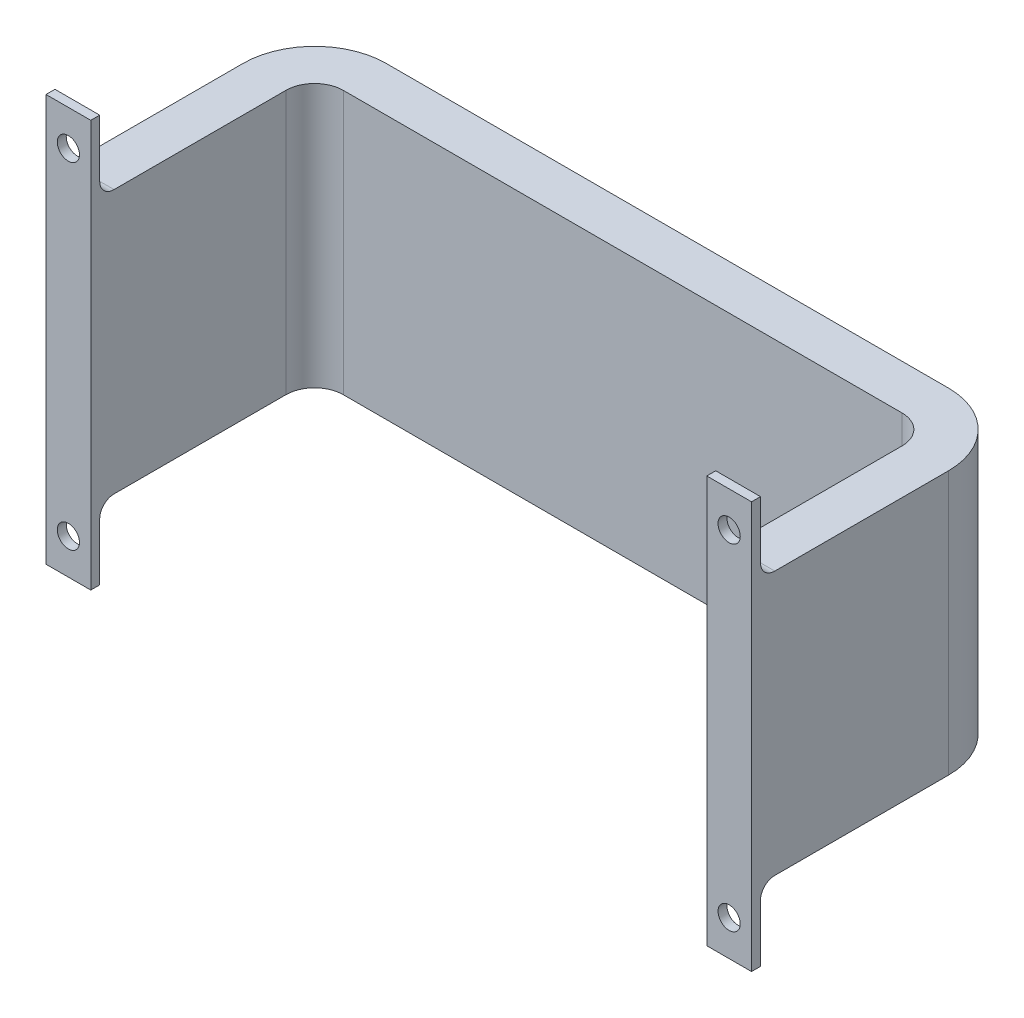
SolidWorks part; units mm, degrees
material "1060 Alloy"
ref_plane "Front Plane" through (0, 0, 0) normal (0, 0, 1) x (1, 0, 0)
ref_plane "Top Plane" through (0, 0, 0) normal (0, 1, 0) x (1, 0, 0)
ref_plane "Right Plane" through (0, 0, 0) normal (1, 0, 0) x (0, 0, -1)
sketch "Sketch1" plane through (0, 0, 0) normal (0, 0, 1) x (1, 0, 0)
  line L1 (125.095, -46.736) -> (-125.095, -46.736)
  line L2 (125.095, -46.736) -> (125.095, 46.736)
  line L3 (125.095, 46.736) -> (-125.095, 46.736)
  line L4 (-125.095, -46.736) -> (-125.095, 46.736)
  line L5 (125.095, -46.736) -> (-125.095, 46.736) construction
  line L6 (125.095, 46.736) -> (-125.095, -46.736) construction
  point P0 (0, 0)
  dimension "D1" = 93.472
  dimension "D2" = 250.19
extrude "Boss-Extrude1" add sketch "Sketch1" along normal blind 95.25
sketch "Sketch5" plane through (0, 0, 95.25) normal (0, 0, 1) x (1, 0, 0)
  line L1 (109.22, -46.736) -> (-109.22, -46.736)
  line L2 (109.22, -46.736) -> (109.22, 46.736)
  line L3 (109.22, 46.736) -> (-109.22, 46.736)
  line L4 (-109.22, -46.736) -> (-109.22, 46.736)
  line L5 (109.22, -46.736) -> (-109.22, 46.736) construction
  line L6 (109.22, 46.736) -> (-109.22, -46.736) construction
  point P0 (0, 0)
  dimension "D1" = 93.472
  dimension "D2" = 218.44
extrude "Cut-Extrude1" cut sketch "Sketch5" against normal blind 79.375
sketch "Sketch6" plane through (0, 0, 95.25) normal (0, 0, 1) x (1, 0, 0)
  line L1 (109.22, 72.136) -> (125.095, 72.136)
  line L2 (109.22, 72.136) -> (109.22, 46.736)
  line L3 (109.22, 46.736) -> (125.095, 46.736)
  line L4 (125.095, 72.136) -> (125.095, 46.736)
  line L5 (109.22, 72.136) -> (125.095, 46.736) construction
  line L6 (109.22, 46.736) -> (125.095, 72.136) construction
  line L8 (125.095, 46.736) -> (109.22, 46.736) construction
  line L9 (125.095, -46.736) -> (125.095, 46.736) construction
  line L11 (0, -51.4096) -> (0, 51.4096) construction
  line L12 (-109.22, 46.736) -> (-125.095, 46.736)
  line L13 (-125.095, 72.136) -> (-125.095, 46.736)
  line L14 (-109.22, 72.136) -> (-125.095, 72.136)
  line L15 (-109.22, 72.136) -> (-109.22, 46.736)
  line L16 (52.3875, 0) -> (-52.3875, 0) construction
  line L17 (109.22, -46.736) -> (125.095, -46.736)
  line L18 (125.095, -72.136) -> (125.095, -46.736)
  line L19 (109.22, -72.136) -> (125.095, -72.136)
  line L20 (109.22, -72.136) -> (109.22, -46.736)
  line L21 (-109.22, -72.136) -> (-109.22, -46.736)
  line L22 (-109.22, -72.136) -> (-125.095, -72.136)
  line L23 (-125.095, -72.136) -> (-125.095, -46.736)
  line L24 (-109.22, -46.736) -> (-125.095, -46.736)
  point P0 (117.1575, 59.436)
  dimension "D1" = 15.875
  dimension "D4" = 25.4
extrude "Boss-Extrude2" add sketch "Sketch6" against normal blind 3.175
sketch "Sketch7" plane through (0, 0, 92.075) normal (0, 0, -1) x (-1, 0, 0)
  line L0 (-125.095, 46.736) -> (125.095, 46.736) construction
  line L3 (117.1575, 59.5376) -> (-145.6767, 59.5376) construction
  line L6 (0, 52.3875) -> (0, -52.3875) construction
  line L7 (52.3875, 0) -> (-52.3875, 0) construction
  line L8 (0, 59.5376) -> (0, -87.3111) construction
  line L9 (-117.1575, -59.5376) -> (117.1575, -59.5376) construction
  circle A0 centre (117.1575, 59.5376) radius 3.937
  circle A1 centre (-117.1575, 59.5376) radius 3.937
  circle A2 centre (117.1575, -59.5376) radius 3.937
  circle A3 centre (-117.1575, -59.5376) radius 3.937
  dimension "D1" = 7.874
  dimension "D2" = 12.8016
  dimension "D3" = 117.1575
extrude "Cut-Extrude2" cut sketch "Sketch7" against normal through all
fillet "Fillet1" radius 25.4 1 edges at (125.095, 0, 0)
fillet "Fillet2" radius 25.4 1 edges at (-125.095, 0, 0)
fillet "Fillet3" radius 5.08 1 edges at (117.1575, 46.736, 92.075)
fillet "Fillet4" radius 5.08 1 edges at (-117.1575, 46.736, 92.075)
fillet "Fillet5" radius 5.08 1 edges at (-117.1575, -46.736, 92.075)
fillet "Fillet6" radius 5.08 1 edges at (117.1575, -46.736, 92.075)
fillet "Fillet7" radius 10.16 1 edges at (-109.22, 0, 15.875)
fillet "Fillet8" radius 10.16 1 edges at (109.22, 0, 15.875)
equation "\"Height\"=3.68"
equation "\"D1@Sketch1\"=\"Height\""
equation "\"D1@Sketch5\"=\"Height\""
